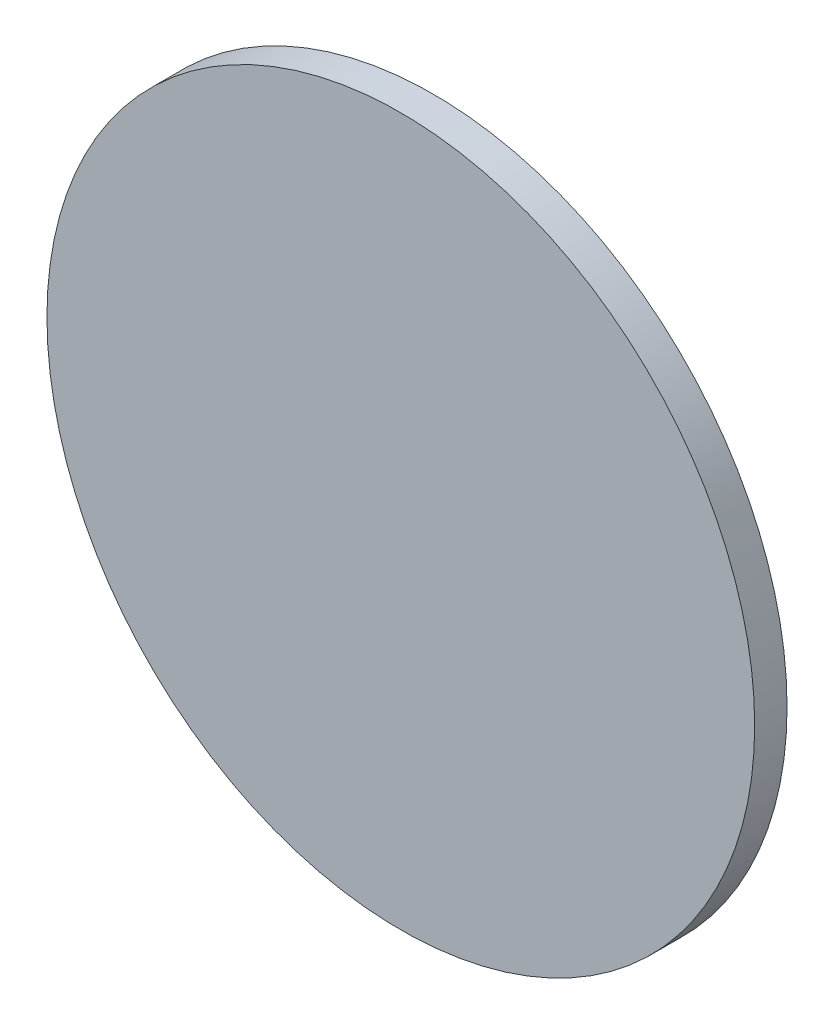
SolidWorks part; units mm, degrees
ref_plane "Front Plane" through (0, 0, 0) normal (0, 0, 1) x (1, 0, 0)
ref_plane "Top Plane" through (0, 0, 0) normal (0, 1, 0) x (1, 0, 0)
ref_plane "Right Plane" through (0, 0, 0) normal (1, 0, 0) x (0, 0, -1)
sketch "Sketch1" plane through (0, 0, -930.4) normal (0, 0, -1) x (-1, 0, 0)
  circle A0 centre (0, 0) radius 17.5
  point P3 (0, 0)
  dimension "D1" = 35
extrude "Boss-Extrude1" add sketch "Sketch1" along normal blind 1.6
